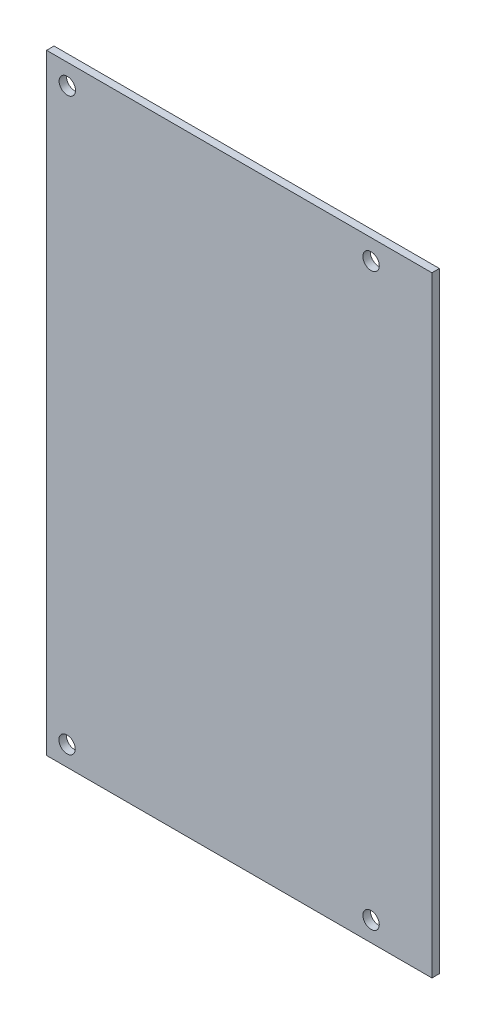
SolidWorks part; units mm, degrees
ref_plane "Front Plane" through (0, 0, 0) normal (0, 0, 1) x (1, 0, 0)
ref_plane "Top Plane" through (0, 0, 0) normal (0, 1, 0) x (1, 0, 0)
ref_plane "Right Plane" through (0, 0, 0) normal (1, 0, 0) x (0, 0, -1)
sketch "Model" plane through (0, 0, 0) normal (0, 0, 1) x (1, 0, 0)
  line L0 (90.5002, 123.101) -> (90.5002, 123.038)
  line L863 (90.5002, 123.101) -> (12.827, 123.101)
  line L864 (90.5002, 0.0508) -> (90.5002, 123.038)
  line L865 (90.5002, 0) -> (90.5002, 0.0508)
  line L866 (12.827, 0) -> (90.5002, 0)
  line L867 (12.827, 0) -> (12.827, 123.101)
  circle A171 centre (17.0002, 118.999) radius 1.65
  circle A172 centre (16.9545, 4.0005) radius 1.65
  circle A173 centre (78.232, 3.999) radius 1.65
  circle A174 centre (78.232, 118.999) radius 1.65
  dimension "D4" = 114.9985
  dimension "D5" = 115
  dimension "D6" = 4.102
  dimension "D7" = 0
  dimension "D2" = 3.3
  dimension "D1" = 77.6732
  dimension "D3" = 61.2318
extrude "Boss-Extrude1" add sketch "Model" along normal blind 1.5 contours L867 L863 L0 L864 L865 L866
